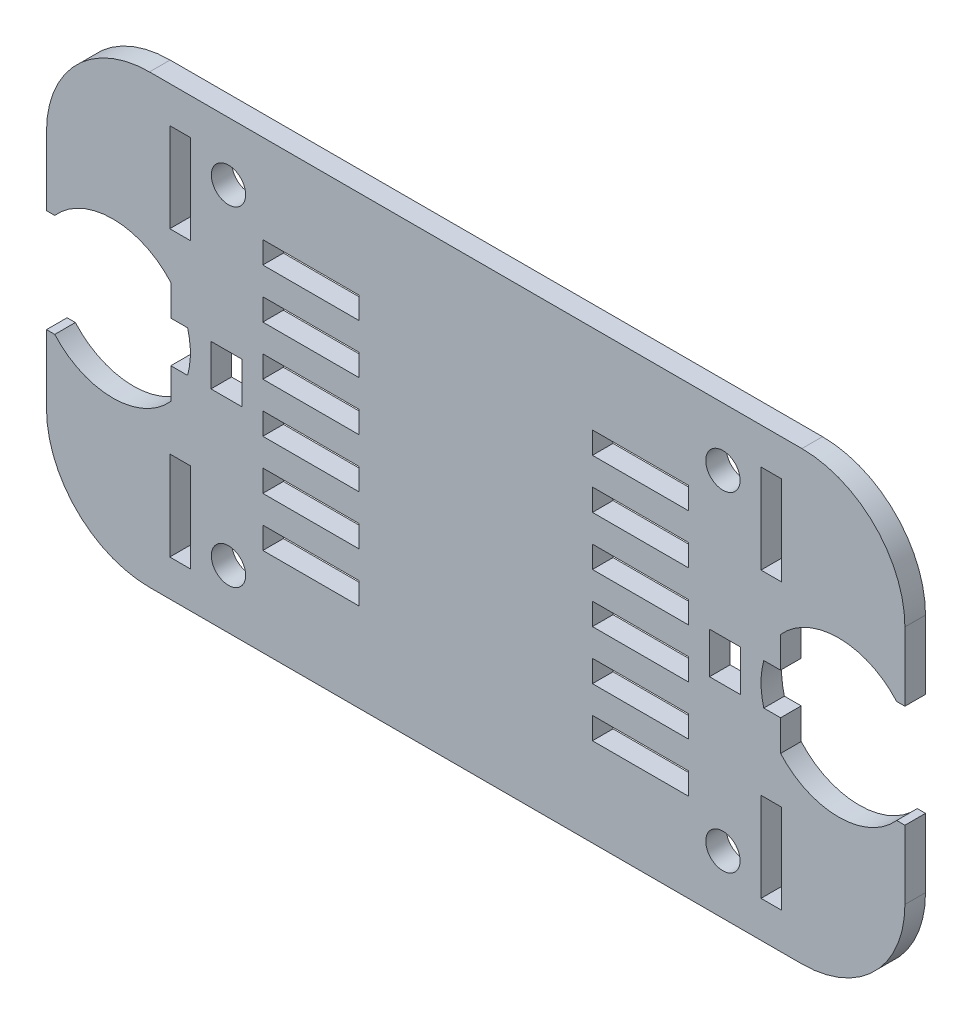
SolidWorks part; units mm, degrees
ref_plane "Přední rovina" through (0, 0, 0) normal (0, 0, 1) x (1, 0, 0)
ref_plane "Horní rovina" through (0, 0, 0) normal (0, 1, 0) x (1, 0, 0)
ref_plane "Pravá rovina" through (0, 0, 0) normal (1, 0, 0) x (0, 0, -1)
sketch "Skica2" plane through (0, 0, 0) normal (0, 0, 1) x (1, 0, 0)
  line L0 (-39.6595, 0) -> (1943.3131, 0) construction
  line L1 (0, -39.6595) -> (0, 1943.3131) construction
  line L2 (-62.5, 7.5) -> (-61.3, 7.5)
  line L3 (-44.3956, 7.5) -> (-44.3956, 3)
  line L4 (-44.3956, -3) -> (-44.3956, -7.5)
  line L5 (-61.3, -7.5) -> (-62.5, -7.5)
  line L6 (-41.5478, 14.2) -> (-41.5478, -3) construction
  line L7 (-62.5, 32.5) -> (62.5, 32.5)
  line L8 (-62.5, 32.5) -> (-62.5, -32.5) construction
  line L9 (-62.5, -32.5) -> (62.5, -32.5)
  line L10 (62.5, 32.5) -> (62.5, -32.5) construction
  line L11 (-62.5, 32.5) -> (62.5, -32.5) construction
  line L12 (-62.5, -32.5) -> (62.5, 32.5) construction
  line L13 (-38.5478, -3) -> (-34.0478, -3)
  line L14 (-38.5478, -3) -> (-38.5478, 3)
  line L15 (-38.5478, 3) -> (-34.0478, 3)
  line L16 (-34.0478, -3) -> (-34.0478, 3)
  line L17 (-38.5478, -3) -> (-34.0478, 3) construction
  line L18 (-38.5478, 3) -> (-34.0478, -3) construction
  line L19 (-44.5478, -14.2) -> (-41.5478, -14.2)
  line L20 (-44.5478, 27.2) -> (-41.5478, 27.2)
  line L21 (-44.5478, 27.2) -> (-44.5478, 14.2)
  line L22 (-44.5478, 14.2) -> (-41.5478, 14.2)
  line L23 (-41.5478, 27.2) -> (-41.5478, 14.2)
  line L24 (-44.5478, -27.2) -> (-44.5478, -14.2)
  line L25 (-44.5478, -27.2) -> (-41.5478, -27.2)
  line L26 (-41.5478, -27.2) -> (-41.5478, -14.2)
  line L27 (-62.5, 7.5) -> (-62.5, 32.5)
  line L28 (-62.5, -7.5) -> (-62.5, -32.5)
  line L29 (44.5478, -27.2) -> (41.5478, -27.2)
  line L30 (44.5478, -27.2) -> (44.5478, -14.2)
  line L31 (41.5478, -27.2) -> (41.5478, -14.2)
  line L32 (44.5478, -14.2) -> (41.5478, -14.2)
  line L33 (44.5478, 14.2) -> (41.5478, 14.2)
  line L34 (44.5478, 27.2) -> (41.5478, 27.2)
  line L35 (41.5478, 27.2) -> (41.5478, 14.2)
  line L36 (44.5478, 27.2) -> (44.5478, 14.2)
  line L37 (34.0478, -3) -> (34.0478, 3)
  line L38 (38.5478, -3) -> (34.0478, -3)
  line L39 (38.5478, -3) -> (38.5478, 3)
  line L40 (38.5478, 3) -> (34.0478, 3)
  line L41 (44.3956, -3) -> (44.3956, -7.5)
  line L42 (44.3956, 7.5) -> (44.3956, 3)
  line L43 (61.3, -7.5) -> (62.5, -7.5)
  line L44 (62.5, 7.5) -> (61.3, 7.5)
  line L45 (62.5, -7.5) -> (62.5, -32.5)
  line L46 (62.5, 7.5) -> (62.5, 32.5)
  line L47 (-44.3956, 3) -> (-41.9533, 3)
  line L48 (-44.3956, -3) -> (-41.9533, -3)
  line L49 (44.3956, -3) -> (41.9533, -3)
  line L50 (44.3956, 3) -> (41.9533, 3)
  line L56 (-31, 19.6) -> (-17, 19.6)
  line L57 (-31, 19.6) -> (-31, 16.4)
  line L58 (-31, 16.4) -> (-17, 16.4)
  line L59 (-17, 19.6) -> (-17, 16.4)
  line L63 (-31, 12.4) -> (-17, 12.4)
  line L64 (-31, 12.4) -> (-31, 9.2)
  line L65 (-31, 9.2) -> (-17, 9.2)
  line L66 (-17, 12.4) -> (-17, 9.2)
  line L71 (-31, 5.2) -> (-17, 5.2)
  line L72 (-31, 5.2) -> (-31, 2)
  line L73 (-31, 2) -> (-17, 2)
  line L74 (-17, 5.2) -> (-17, 2)
  line L87 (-17, -5.2) -> (-17, -2)
  line L88 (-31, -2) -> (-17, -2)
  line L89 (-31, -5.2) -> (-31, -2)
  line L90 (-31, -5.2) -> (-17, -5.2)
  line L91 (-17, -12.4) -> (-17, -9.2)
  line L92 (-31, -9.2) -> (-17, -9.2)
  line L93 (-31, -12.4) -> (-31, -9.2)
  line L94 (-31, -12.4) -> (-17, -12.4)
  line L95 (-31, -16.4) -> (-17, -16.4)
  line L96 (-17, -19.6) -> (-17, -16.4)
  line L97 (-31, -19.6) -> (-31, -16.4)
  line L98 (-31, -19.6) -> (-17, -19.6)
  line L99 (31, -19.6) -> (17, -19.6)
  line L100 (31, -19.6) -> (31, -16.4)
  line L101 (31, -16.4) -> (17, -16.4)
  line L102 (17, -19.6) -> (17, -16.4)
  line L103 (31, -12.4) -> (17, -12.4)
  line L104 (31, -12.4) -> (31, -9.2)
  line L105 (31, -9.2) -> (17, -9.2)
  line L106 (17, -12.4) -> (17, -9.2)
  line L107 (17, -5.2) -> (17, -2)
  line L108 (31, -5.2) -> (17, -5.2)
  line L109 (31, -5.2) -> (31, -2)
  line L110 (31, -2) -> (17, -2)
  line L111 (17, 5.2) -> (17, 2)
  line L112 (31, 2) -> (17, 2)
  line L113 (31, 5.2) -> (31, 2)
  line L114 (31, 5.2) -> (17, 5.2)
  line L115 (31, 9.2) -> (17, 9.2)
  line L116 (31, 12.4) -> (31, 9.2)
  line L117 (31, 12.4) -> (17, 12.4)
  line L118 (17, 12.4) -> (17, 9.2)
  line L119 (31, 16.4) -> (17, 16.4)
  line L120 (31, 19.6) -> (31, 16.4)
  line L121 (17, 19.6) -> (17, 16.4)
  line L122 (31, 19.6) -> (17, 19.6)
  arc A0 (-44.3956, 7.5) -> (-61.3, 7.5) centre (-52.8478, 0) ccw
  arc A2 (-61.3, -7.5) -> (-44.3956, -7.5) centre (-52.8478, 0) ccw
  circle A3 centre (-52.8478, 0) radius 11.3 construction
  arc A5 (44.3956, 7.5) -> (61.3, 7.5) centre (52.8478, 0) cw
  arc A6 (61.3, -7.5) -> (44.3956, -7.5) centre (52.8478, 0) cw
  arc A19 (-41.9533, 3) -> (-41.9533, -3) centre (-52.8478, 0) cw
  arc A20 (41.9533, 3) -> (41.9533, -3) centre (52.8478, 0) ccw
  circle A21 centre (-36, 24) radius 2.5
  circle A22 centre (36, 24) radius 2.5
  circle A23 centre (-36, -24) radius 2.5
  circle A24 centre (36, -24) radius 2.5
  point P15 (-36.2978, 0)
  point P26 (0, 0)
  dimension "D1" = 22.6
  dimension "D2" = 6
  dimension "D17" = 72
  dimension "D19" = 17
  dimension "D13" = 36
  dimension "D15" = 24
  dimension "D33" = 5
  dimension "D34" = 5
  dimension "D35" = 5
  dimension "D36" = 5
  dimension "D3" = 15
  dimension "D4" = 1.2
  dimension "D5" = 125
  dimension "D6" = 65
  dimension "D7" = 6
  dimension "D8" = 4.5
  dimension "D9" = 3
  dimension "D10" = 13
  dimension "D11" = 3
  dimension "D12" = 14.2
  dimension "D14" = 36
  dimension "D16" = 24
  dimension "D18" = 24
  dimension "D20" = 14
  dimension "D21" = 3.2
  dimension "D22" = 2
  dimension "D23" = 4
  dimension "D24" = 4
  dimension "D25" = 3.2
  dimension "D26" = 3.2
  dimension "D27" = 17
  dimension "D28" = 17
  dimension "D29" = 14
  dimension "D30" = 14
  dimension "D31" = 5.5478
  dimension "D32" = 5.5478
extrude "Přidat vysunutím1" add sketch "Skica2" along normal blind 3
fillet "Zaoblit1" radius 15 4 edges at (62.5, -32.5, 1.5) (-62.5, -32.5, 1.5) (62.5, 32.5, 1.5) (-62.5, 32.5, 1.5)
